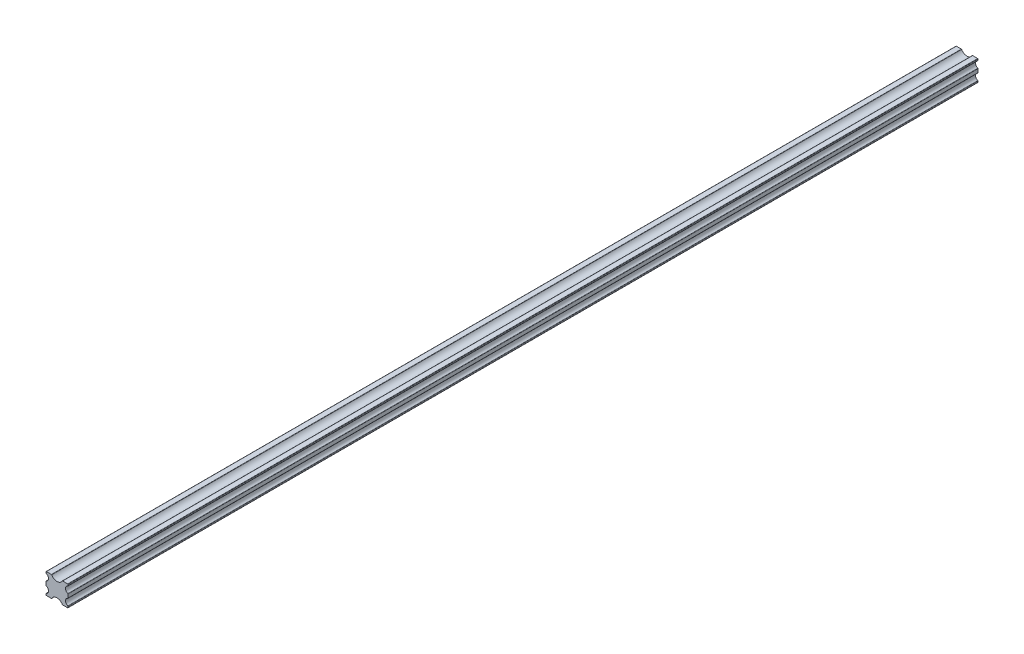
SolidWorks part; units mm, degrees
ref_plane "Front Plane" through (0, 0, 0) normal (0, 0, 1) x (1, 0, 0)
ref_plane "Top Plane" through (0, 0, 0) normal (0, 1, 0) x (1, 0, 0)
ref_plane "Right Plane" through (0, 0, 0) normal (1, 0, 0) x (0, 0, -1)
sketch "Sketch1" plane through (0, 0, 0) normal (0, 0, 1) x (1, 0, 0)
  line L1 (-6.05, -5.7) -> (6.05, -5.7)
  line L2 (-6.05, -5.7) -> (-6.05, 5.7)
  line L3 (-6.05, 5.7) -> (6.05, 5.7)
  line L4 (6.05, -5.7) -> (6.05, 5.7)
  line L5 (-6.05, -5.7) -> (6.05, 5.7) construction
  line L6 (-6.05, 5.7) -> (6.05, -5.7) construction
  point P0 (0, 0)
  dimension "D1" = 11.4
  dimension "D2" = 12.1
extrude "Boss-Extrude1" add sketch "Sketch1" along normal blind 500
sketch "Sketch2" plane through (0, 0, 500) normal (0, 0, 1) x (1, 0, 0)
  line L0 (6.05, 5.7) -> (-6.05, 5.7) construction
  line L1 (-6.05, 0) -> (6.05, 0) construction
  line L2 (-6.05, 5.7) -> (-6.05, -5.7) construction
  line L3 (6.05, -5.7) -> (6.05, 5.7) construction
  line L4 (0, 5.7) -> (0, -5.7) construction
  line L5 (-6.05, -5.7) -> (6.05, -5.7) construction
  circle A0 centre (0, 7.279) radius 3.379
  circle A1 centre (0, -7.279) radius 3.379
  circle A2 centre (-6.565, 2.9302) radius 1.9
  circle A3 centre (-6.565, -2.9302) radius 1.9
  circle A4 centre (6.565, -2.9302) radius 1.9
  circle A5 centre (6.565, 2.9302) radius 1.9
  dimension "D1" = 6.758
  dimension "D3" = 3.8
  dimension "D2" = 1.579
  dimension "D4" = 0.515
extrude "Cut-Extrude1" cut sketch "Sketch2" against normal through all
fillet "Fillet1" radius 0.2 16 edges at (6.05, 5.7, 250) (6.05, 4.759, 250) (6.05, 1.1013, 250) (6.05, -1.1013, 250) (6.05, -4.759, 250) (6.05, -5.7, 250) (-2.9874, 5.7, 250) (2.9874, 5.7, 250) (2.9874, -5.7, 250) (-2.9874, -5.7, 250) (-6.05, -5.7, 250) (-6.05, -4.759, 250) (-6.05, -1.1013, 250) (-6.05, 1.1013, 250) (-6.05, 4.759, 250) (-6.05, 5.7, 250)
